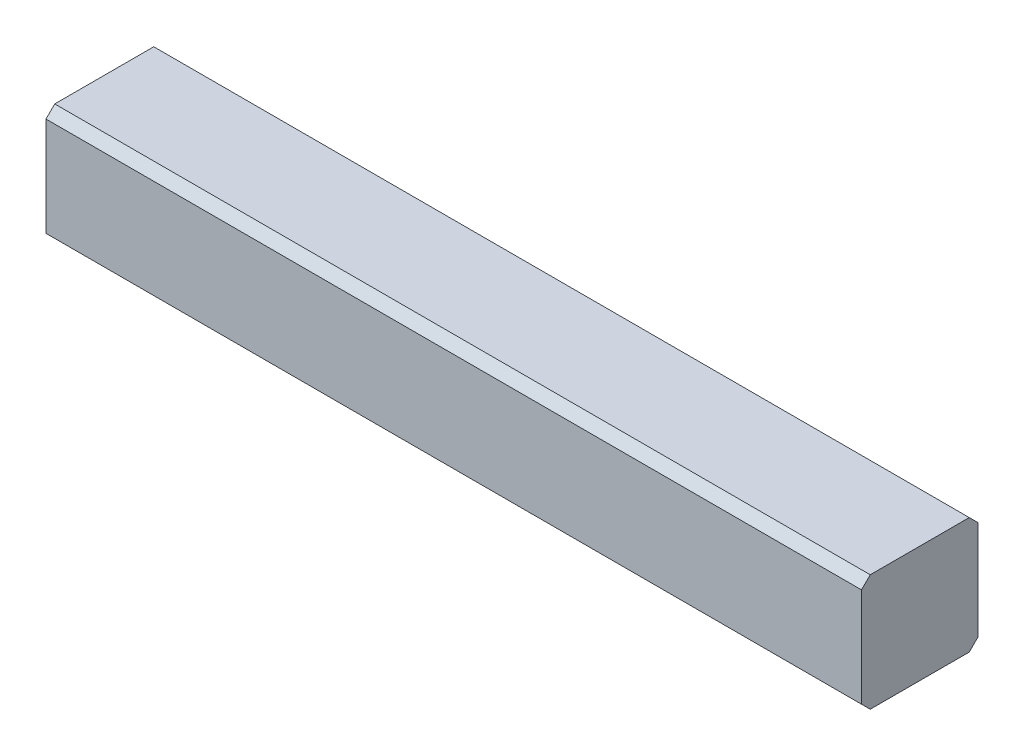
SolidWorks part; units mm, degrees
material "Alloy Steel"
ref_plane "Front Plane" through (0, 0, 0) normal (0, 0, 1) x (1, 0, 0)
ref_plane "Top Plane" through (0, 0, 0) normal (0, 1, 0) x (1, 0, 0)
ref_plane "Right Plane" through (0, 0, 0) normal (1, 0, 0) x (0, 0, -1)
sketch "Sketch1" plane through (0, 0, 0) normal (1, 0, 0) x (0, 0, -1)
  line L0 (-0.85, 1) -> (-1, 0.85)
  line L1 (-0.85, 1) -> (0.85, 1)
  line L2 (-1, 0.85) -> (-1, -0.85)
  line L3 (-0.85, -1) -> (0.85, -1)
  line L4 (1, 0.85) -> (1, -0.85)
  line L5 (-1, 1) -> (1, -1) construction
  line L6 (-1, -1) -> (1, 1) construction
  line L7 (-1, -0.85) -> (-0.85, -1)
  line L8 (0.85, -1) -> (1, -0.85)
  line L9 (0.85, 1) -> (1, 0.85)
  point P0 (0, 0)
  dimension "D1" = 2
  dimension "D2" = 2
extrude "Boss-Extrude1" add sketch "Sketch1" along normal blind 14
